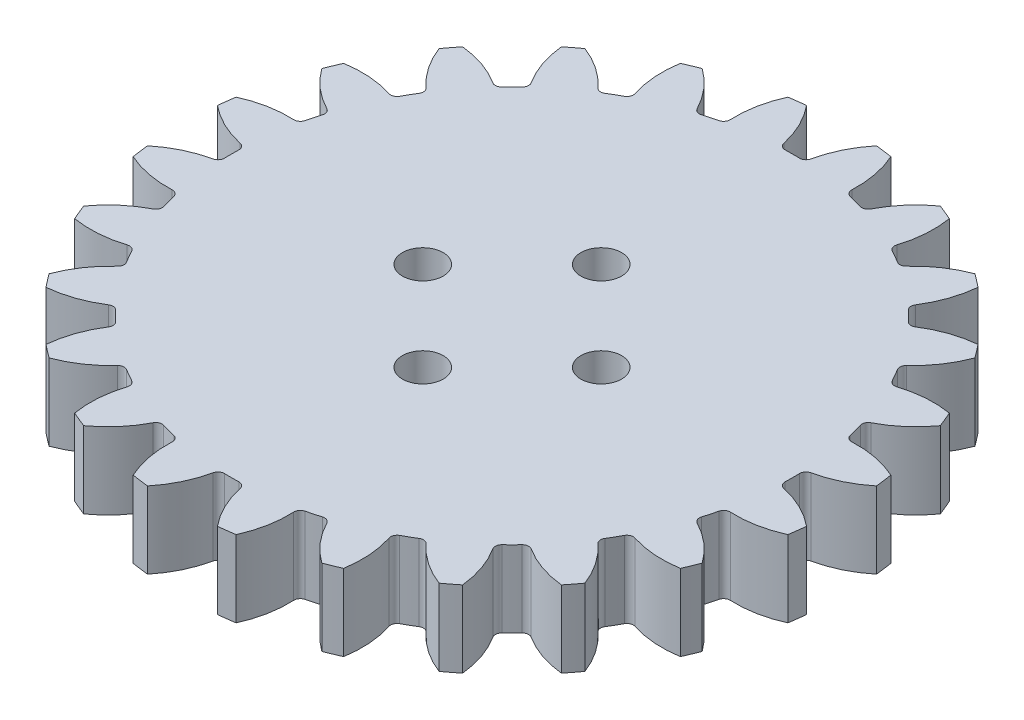
SolidWorks part; units mm, degrees
ref_plane "前视基准面" through (0, 0, 0) normal (0, 0, 1) x (1, 0, 0)
ref_plane "上视基准面" through (0, 0, 0) normal (0, 1, 0) x (1, 0, 0)
ref_plane "右视基准面" through (0, 0, 0) normal (1, 0, 0) x (0, 0, -1)
other "Configuration Table"
sketch "草图1" plane through (0, 0, 0) normal (0, 1, 0) x (1, 0, 0)
  circle A0 centre (0, 0) radius 26
  dimension "D1" = 52
extrude "凸台-拉伸1" add sketch "草图1" along normal blind 6
sketch "草图2" plane through (0, 0, 0) normal (0, 1, 0) x (1, 0, 0)
  line L0 (0, 32.5284) -> (0, -27.4432) construction
  line L1 (0, 0) -> (2.2127, 33.7594) construction
  line L2 (1.5697, 23.9486) -> (24.0107, 22.4778) construction
  line L3 (1.5697, 23.9486) -> (26.0747, 13.1661) construction
  line L4 (0, 0) -> (9.083, 20.6427) construction
  circle A0 centre (0, 0) radius 24 construction
  arc A1 (0.5605, 21.9929) -> (-0.5605, 21.9929) centre (0, 0) ccw
  arc A2 (2.7418, 25.855) -> (-2.7418, 25.855) centre (0, 0) ccw
  circle A3 centre (0, 0) radius 26 construction
  arc A4 (2.7418, 25.855) -> (1.0619, 22.3865) centre (9.083, 20.6427) ccw
  arc A5 (1.0619, 22.3865) -> (0.5605, 21.9929) centre (0.5733, 22.4927) cw
  arc A6 (-1.0619, 22.3865) -> (-0.5605, 21.9929) centre (-0.5733, 22.4927) ccw
  arc A7 (-2.7418, 25.855) -> (-1.0619, 22.3865) centre (-9.083, 20.6427) cw
  dimension "D2" = 48
  dimension "D4" = 22
  dimension "D5" = 0.5
  dimension "D1" = 3.75
  dimension "D3" = 20
extrude "切除-拉伸1" cut sketch "草图2" along normal through all
pattern_circular "阵列(圆周)1" count 24 over 360 about axis through (0, 0, 0) along (0, 1, 0) of "切除-拉伸1"
sketch "草图3" plane through (0, 0, 0) normal (0, 1, 0) x (1, 0, 0)
  circle A0 centre (0, 0) radius 7 construction
  circle A1 centre (0, 7) radius 1.6
  circle A2 centre (7, 0) radius 1.6
  circle A3 centre (0, -7) radius 1.6
  circle A4 centre (-7, 0) radius 1.6
  point P14 (0, 0)
  dimension "D1" = 14
  dimension "D2" = 3.2
  dimension "D3" = 4
extrude "切除-拉伸2" cut sketch "草图3" along normal through all
sketch "草图4" plane through (0, 0, 0) normal (0, 1, 0) x (1, 0, 0)
  circle A0 centre (0, 0) radius 24 construction
  dimension "D1" = 48
